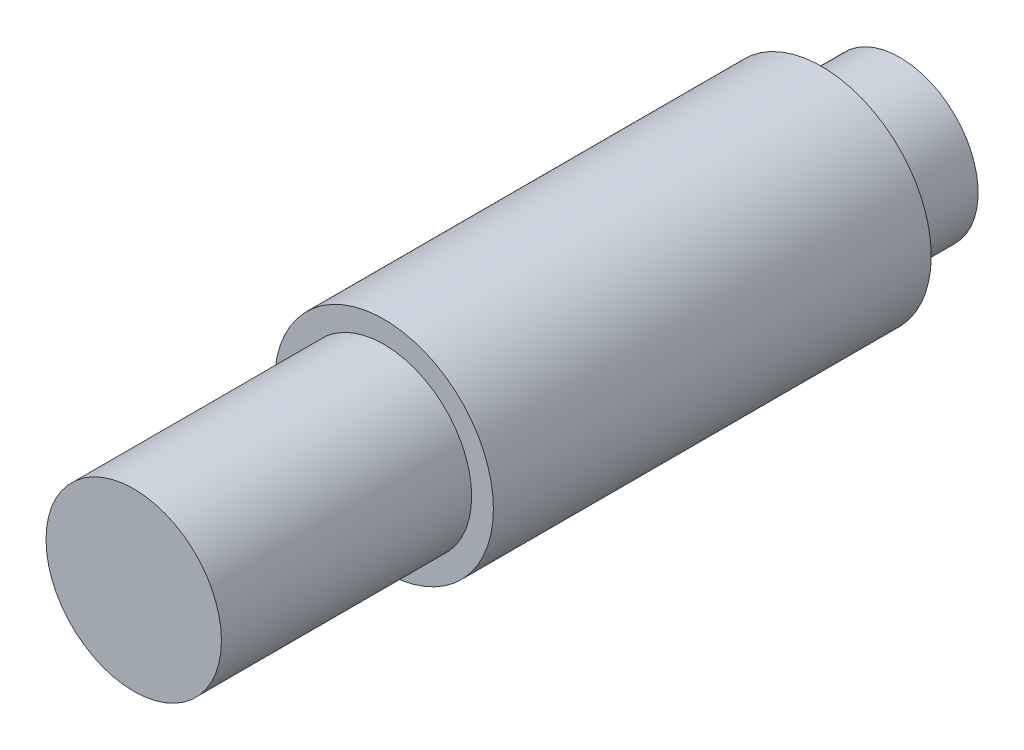
SolidWorks part; units mm, degrees
ref_plane "Front Plane" through (0, 0, 0) normal (0, 0, 1) x (1, 0, 0)
ref_plane "Top Plane" through (0, 0, 0) normal (0, 1, 0) x (1, 0, 0)
ref_plane "Right Plane" through (0, 0, 0) normal (1, 0, 0) x (0, 0, -1)
sketch "Sketch1" plane through (0, 0, 0) normal (0, 0, 1) x (1, 0, 0)
  circle A1 centre (0, 0) radius 23.5 construction
  circle A2 centre (0, 0) radius 17.5
  dimension "D1" = 35
extrude "Boss-Extrude1" add sketch "Sketch1" along normal blind 70
sketch "Sketch2" plane through (0, 0, 70) normal (0, 0, 1) x (1, 0, 0)
  circle A0 centre (0, 0) radius 14.025
extrude "Boss-Extrude2" add sketch "Sketch2" along normal blind 40
sketch "Sketch4" plane through (0, 0, 0) normal (0, 0, -1) x (-1, 0, 0)
  circle A0 centre (0, 0) radius 12.5
  dimension "D1" = 25
extrude "Boss-Extrude3" add sketch "Sketch4" along normal blind 12.5
sketch3d "3DSketch1"
  line L0 (0, 0, 110) -> (0, 0, -12.5) construction
  line L1 (0, 0, 110) -> (0, 0, 70) construction
  line L2 (0, 0, -12.5) -> (0, 0, 0) construction
  line L3 (0, 0, -12.5) -> (0, 0, -83.5963) construction
  line L4 (0, 0, 110) -> (0, 0, 197.1641) construction
sketch "Sketch5" plane through (0, 0, -12.5) normal (0, 0, -1) x (-1, 0, 0)
  circle A0 centre (0, 0) radius 164
  dimension "D1" = 328
